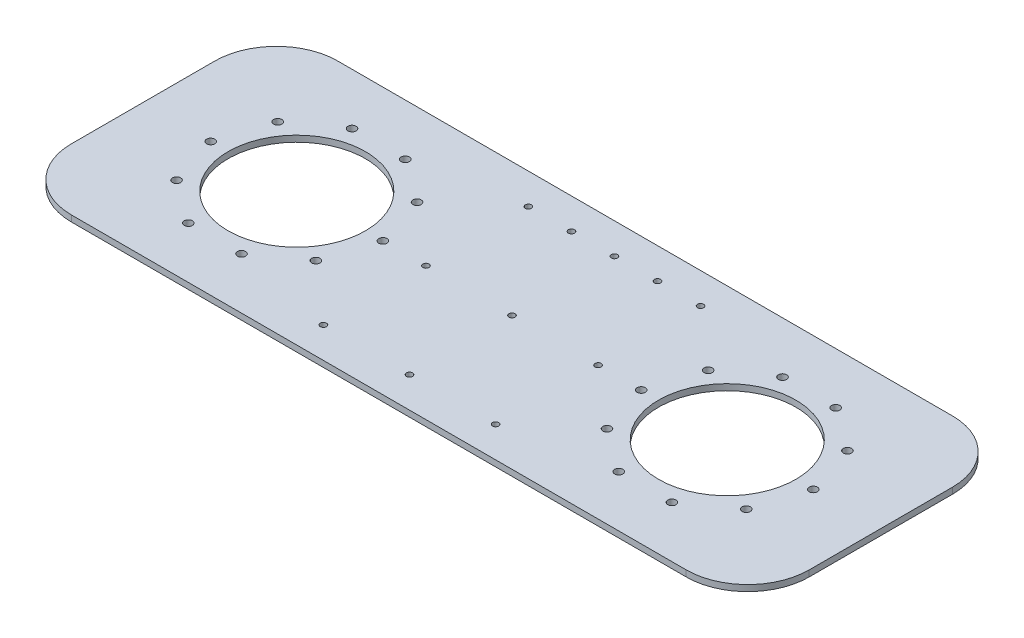
SolidWorks part; units mm, degrees
ref_plane "前基準面" through (0, 0, 0) normal (0, 0, 1) x (1, 0, 0)
ref_plane "上基準面" through (0, 0, 0) normal (0, 1, 0) x (1, 0, 0)
ref_plane "右基準面" through (0, 0, 0) normal (1, 0, 0) x (0, 0, -1)
sketch "草圖1" plane through (0, 0, 0) normal (0, 1, 0) x (1, 0, 0)
  line L0 (-105, 0) -> (105, 0) construction
  line L1 (-150, 65) -> (150, 65)
  line L2 (-180, 35) -> (-180, -35)
  line L3 (-150, -65) -> (150, -65)
  line L4 (180, 35) -> (180, -35)
  line L5 (-180, 65) -> (180, -65) construction
  line L6 (-180, -65) -> (180, 65) construction
  circle A0 centre (105, 0) radius 33.5
  circle A1 centre (-105, 0) radius 33.5
  arc A2 (150, 65) -> (180, 35) centre (150, 35) cw
  arc A3 (180, -35) -> (150, -65) centre (150, -35) cw
  arc A4 (-150, -65) -> (-180, -35) centre (-150, -35) cw
  arc A5 (-180, 35) -> (-150, 65) centre (-150, 35) cw
  point P0 (0, 0)
  dimension "D3" = 67
  dimension "D5" = 30
  dimension "D1" = 360
  dimension "D2" = 130
  dimension "D4" = 210
extrude "填料-伸長1" add sketch "草圖1" along normal blind 3
sketch "草圖3" plane through (0, 3, 0) normal (0, 1, 0) x (1, 0, 0)
  circle A0 centre (-105, 0) radius 42 construction
  circle A1 centre (-63, 0) radius 2
  dimension "D1" = 84
  dimension "D2" = 4
extrude "除料-伸長1" cut sketch "草圖3" against normal up to next
pattern_circular "環狀複製排列1" count 10 over 360 about axis through (-105, 0, 0) along (0, 1, 0) of "除料-伸長1"
mirror "鏡射1" about plane through (0, 0, 0) normal (1, 0, 0) of "除料-伸長1", "環狀複製排列1"
sketch "草圖4" plane through (0, 3, 0) normal (0, 1, 0) x (1, 0, 0)
  line L1 (-41, 33) -> (41, 33) construction
  line L2 (-41, 33) -> (-41, -33) construction
  line L3 (-41, -33) -> (41, -33) construction
  line L4 (41, 33) -> (41, -33) construction
  line L5 (-41, 33) -> (41, -33) construction
  line L6 (-41, -33) -> (41, 33) construction
  line L7 (-50, 54) -> (50, 54) construction
  line L8 (-50, 54) -> (-50, 46) construction
  line L9 (-50, 46) -> (50, 46) construction
  line L10 (50, 54) -> (50, 46) construction
  line L11 (-50, 54) -> (50, 46) construction
  line L12 (-50, 46) -> (50, 54) construction
  circle A0 centre (42, 50) radius 1.5
  point P0 (0, 0)
  point P6 (0, 50)
  dimension "D6" = 3
  dimension "D1" = 82
  dimension "D2" = 66
  dimension "D3" = 8
  dimension "D4" = 100
  dimension "D5" = 50
  dimension "D7" = 8
extrude "除料-伸長2" cut sketch "草圖4" against normal up to next
pattern_linear "直線複製排列1" count 5 spacing 21 along (-1, 0, 0) of "除料-伸長2"
sketch "草圖5" plane through (0, 3, 0) normal (0, 1, 0) x (1, 0, 0)
  circle A0 centre (42, 0) radius 1.5
  circle A1 centre (0, 0) radius 1.5
  circle A2 centre (-42, 0) radius 1.5
  circle A3 centre (42, 50) radius 1.5 construction
  point P8 (0, 50)
  point P9 (42, 50)
  point P13 (-42, 50)
  dimension "D1" = 50
extrude "除料-伸長3" cut sketch "草圖5" against normal up to next
pattern_linear "直線複製排列2" count 2 spacing 50 along (0, 0, 1) of "除料-伸長3"
